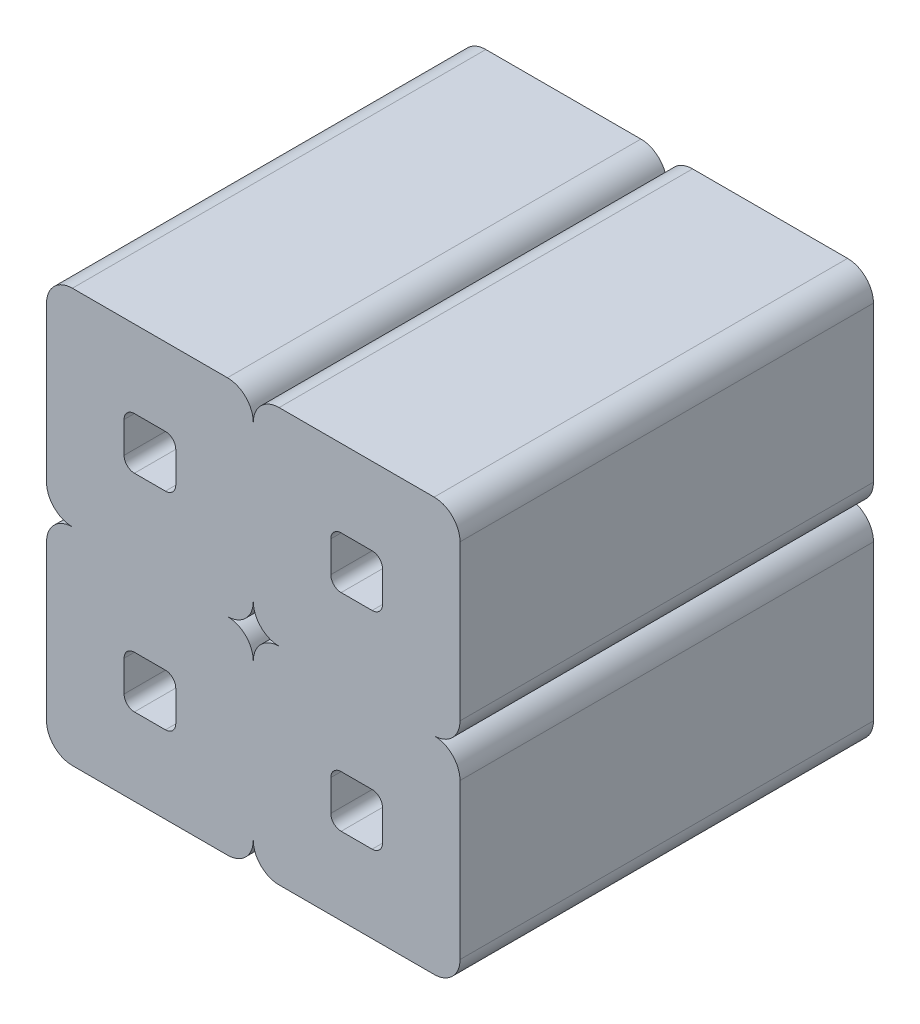
SolidWorks part; units mm, degrees
ref_plane "前视基准面" through (0, 0, 0) normal (0, 0, 1) x (1, 0, 0)
ref_plane "上视基准面" through (0, 0, 0) normal (0, 1, 0) x (1, 0, 0)
ref_plane "右视基准面" through (0, 0, 0) normal (1, 0, 0) x (0, 0, -1)
sketch "草图1" plane through (0, 0, 0) normal (0, 0, 1) x (1, 0, 0)
  line L0 (1, 0) -> (1, -2) construction
  line L1 (0.25, 0) -> (1.75, 0)
  line L2 (0, -0.25) -> (0, -1.75)
  line L3 (0.25, -2) -> (1.75, -2)
  line L4 (2, -0.25) -> (2, -1.75)
  line L5 (0, -1) -> (2, -1) construction
  line L7 (0.85, -0.75) -> (1.15, -0.75)
  line L8 (0.75, -0.85) -> (0.75, -1.15)
  line L9 (0.85, -1.25) -> (1.15, -1.25)
  line L10 (1.25, -0.85) -> (1.25, -1.15)
  arc A0 (2, -1.75) -> (1.75, -2) centre (1.75, -1.75) cw
  arc A1 (0.25, -2) -> (0, -1.75) centre (0.25, -1.75) cw
  arc A2 (0.25, 0) -> (0, -0.25) centre (0.25, -0.25) ccw
  arc A3 (2, -0.25) -> (1.75, 0) centre (1.75, -0.25) ccw
  circle A4 centre (1, -1) radius 0.25 construction
  arc A5 (0.75, -1.15) -> (0.85, -1.25) centre (0.85, -1.15) ccw
  arc A6 (1.15, -1.25) -> (1.25, -1.15) centre (1.15, -1.15) ccw
  arc A7 (1.25, -0.85) -> (1.15, -0.75) centre (1.15, -0.85) ccw
  arc A8 (0.85, -0.75) -> (0.75, -0.85) centre (0.85, -0.85) ccw
  point P11 (0, 0)
  dimension "D3" = 0.25
  dimension "D4" = 0.5
  dimension "D5" = 0.1
  dimension "D1" = 2
  dimension "D2" = 2
extrude "凸台-拉伸1" add sketch "草图1" along normal blind 4
pattern_linear "阵列(线性)2" count 2 spacing 2 along (1, 0, 0) count 2 spacing 2 along (0, -1, 0) of "凸台-拉伸1"
sketch "草图3" plane through (0, 0, 0) normal (0, 0, -1) x (-1, 0, 0)
  line L0 (-1, 0) -> (-1, -4) construction
  line L1 (-1.75, 0) -> (-0.25, 0) construction
  line L2 (-0.25, -4) -> (-1.75, -4) construction
  line L3 (0, -1) -> (-2.4529, -1) construction
  line L4 (0, -0.25) -> (0, -1.75) construction
  line L5 (-0.25, -2) -> (-1.75, -2) construction
  line L9 (-0.75, -0.85) -> (-0.75, -1.15)
  line L10 (-0.85, -1.25) -> (-1.15, -1.25)
  line L11 (-1.25, -0.85) -> (-1.25, -1.15)
  line L12 (-0.85, -0.75) -> (-1.15, -0.75)
  arc A4 (-1.25, -1.15) -> (-1.15, -1.25) centre (-1.15, -1.15) ccw
  arc A5 (-0.75, -1.15) -> (-0.85, -1.25) centre (-0.85, -1.15) cw
  arc A6 (-0.85, -0.75) -> (-0.75, -0.85) centre (-0.85, -0.85) cw
  arc A7 (-1.15, -0.75) -> (-1.25, -0.85) centre (-1.15, -0.85) ccw
  point P26 (-1, -1.25)
  point P28 (-0.75, -1)
  point P29 (-1.25, -1)
  point P31 (-1.25, -1.25)
  point P34 (-0.75, -1.25)
  point P37 (-0.75, -0.75)
  point P40 (-1.25, -0.75)
  dimension "D4" = 0.1
  dimension "D2" = 0.5
  dimension "D3" = 0.5
ref_plane "基准面1" through (1, 0, 0) normal (-1, 0, 0) x (0, 0, 1)
sketch "草图4" plane through (1, 0, 0) normal (-1, 0, 0) x (0, 0, 1)
  line L0 (0, -1.2503) -> (-0.7, -1.2503)
  line L1 (-0.8, -1.1503) -> (-0.8, 0.5)
  line L2 (0, 0) -> (0, -4) construction
  line L3 (0, 0) -> (0, -2) construction
  line L5 (-1.9741, 0.5) -> (2.5979, 0.5) construction
  line L6 (4, 0) -> (0, 0) construction
  arc A0 (-0.7, -1.2503) -> (-0.8, -1.1503) centre (-0.7, -1.1503) cw
  dimension "D3" = 0.1
  dimension "D1" = 0.8
  dimension "D2" = 0.5
ref_plane "基准面2" through (0, -2, 0) normal (0, -1, 0) x (1, 0, 0)
sketch "草图5" plane through (0, 0, 0) normal (0, 0, -1) x (-1, 0, 0)
  line L0 (-0.75, -0.85) -> (-0.75, -1.15)
  line L1 (-1.15, -0.75) -> (-0.85, -0.75)
  line L2 (-1.25, -0.85) -> (-1.25, -1.15)
  line L3 (-1.15, -1.25) -> (-0.85, -1.25)
  arc A0 (-1.15, -0.75) -> (-1.25, -0.85) centre (-1.15, -0.85) ccw
  arc A1 (-0.85, -0.75) -> (-0.75, -0.85) centre (-0.85, -0.85) cw
  arc A2 (-0.85, -1.25) -> (-0.75, -1.15) centre (-0.85, -1.15) ccw
  arc A3 (-1.25, -1.15) -> (-1.15, -1.25) centre (-1.15, -1.15) ccw
  dimension "D1" = 0.1
  dimension "D2" = 0.1
  dimension "D3" = 0.1
  dimension "D4" = 0.1
extrude "凸台-拉伸3" add sketch "草图5" along normal blind 0.4 and the other way blind 1 separate body
pattern_linear "阵列(线性)11" count 2 spacing 2 along (1, 0, 0) count 2 spacing 2 along (0, -1, 0) of "凸台-拉伸3"
